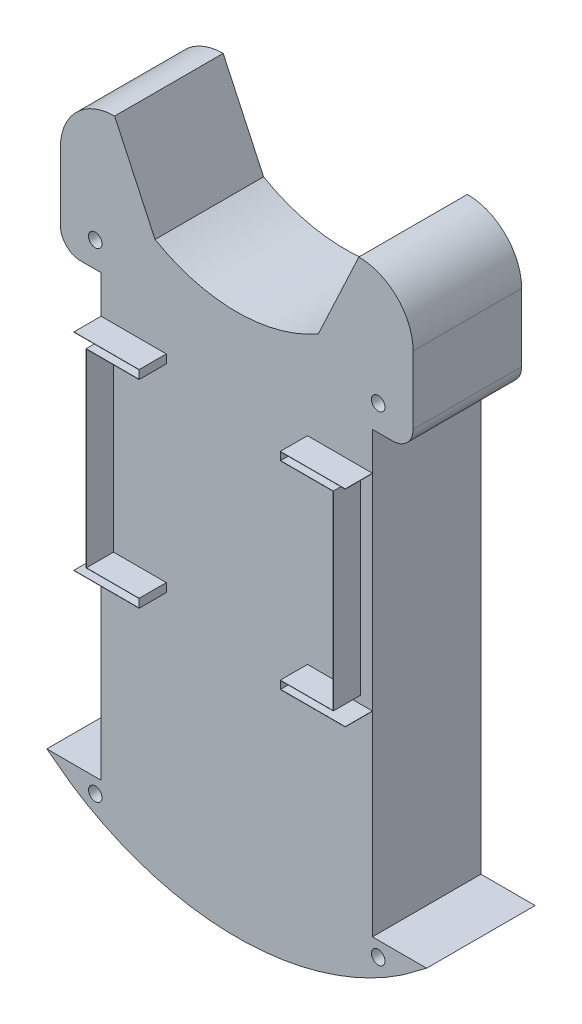
SolidWorks part; units mm, degrees
ref_plane "Front Plane" through (0, 0, 0) normal (0, 0, 1) x (1, 0, 0)
ref_plane "Top Plane" through (0, 0, 0) normal (0, 1, 0) x (1, 0, 0)
ref_plane "Right Plane" through (0, 0, 0) normal (1, 0, 0) x (0, 0, -1)
sketch "Sketch2" plane through (0, 0, 0) normal (0, 0, 1) x (1, 0, 0)
  line L1 (1270, 1959.5385) -> (1270, -2155.2615)
  line L2 (1270, -2155.2615) -> (1778, -2155.2615)
  line L3 (1778, -2155.2615) -> (1548.5652, -2325.5928)
  line L4 (0, 1050.9467) -> (0, -1390.1401) construction
  line L5 (1270, 1959.5385) -> (1460.5, 1959.5385)
  line L6 (1651, 2150.0385) -> (1651, 2785.0385)
  line L7 (-1778, -2155.2615) -> (-1548.5652, -2325.5928)
  line L8 (-1270, -2155.2615) -> (-1778, -2155.2615)
  line L9 (-1270, 1959.5385) -> (-1270, -2155.2615)
  line L10 (-1651, 2150.0385) -> (-1651, 2785.0385)
  line L11 (-1270, 1959.5385) -> (-1460.5, 1959.5385)
  line L12 (-1143, 3293.0385) -> (-764.6087, 2481.5759)
  line L14 (1143, 3293.0385) -> (764.6087, 2481.5759)
  line L15 (1143, 3293.0385) -> (1143, 2886.1422) construction
  arc A1 (1460.5, 1959.5385) -> (1651, 2150.0385) centre (1460.5, 2150.0385) ccw
  arc A2 (1651, 2785.0385) -> (1143, 3293.0385) centre (1143, 2785.0385) ccw
  arc A3 (-1651, 2785.0385) -> (-1143, 3293.0385) centre (-1143, 2785.0385) cw
  arc A4 (-1460.5, 1959.5385) -> (-1651, 2150.0385) centre (-1460.5, 2150.0385) cw
  arc A5 (-1778, -2155.2615) -> (1548.5652, -2325.5928) centre (0, 0) ccw
  arc A7 (-764.6087, 2481.5759) -> (764.6087, 2481.5759) centre (0, 3799.889) ccw
  point P21 (-1460.5, 1959.5385)
  dimension "D1" = 4114.8
  dimension "D4" = 2794
  dimension "D6" = 508
  dimension "D8" = 190.5
  dimension "D10" = 895.35
  dimension "D12" = 25
  dimension "D11" = 1524
  dimension "D13" = 2794
  dimension "D2" = 508
  dimension "D3" = 285.75
  dimension "D5" = 190.5
  dimension "D7" = 1270
  dimension "D9" = 635
extrude "Boss-Extrude1" add sketch "Sketch2" along normal blind 1016 contours A7 L12 A3 L10 A4 L11 L9 L8 L7 A5 L3 L2 L1 L5 A1 L6 A2 L14
sketch "Sketch5" plane through (0, 0, 1016) normal (0, 0, 1) x (1, 0, 0)
  line L0 (1270, -326.4615) -> (662.1255, -326.4615)
  line L1 (1270, 1959.5385) -> (1270, -2155.2615) construction
  line L3 (662.1255, -326.4615) -> (662.1255, -250.2615)
  line L6 (662.1255, -250.2615) -> (1155.7, -250.2615)
  line L7 (1155.7, -250.2615) -> (1155.7, 1527.7385)
  line L8 (1155.7, 1527.7385) -> (662.1255, 1527.7385)
  line L9 (662.1255, 1527.7385) -> (662.1255, 1603.9385)
  line L10 (662.1255, 1603.9385) -> (1270, 1603.9385)
  line L11 (1270, -2155.2615) -> (1778, -2155.2615) construction
  line L13 (0, 867.6729) -> (0, -443.3851) construction
  line L14 (-662.1255, 1603.9385) -> (-1270, 1603.9385)
  line L15 (-662.1255, 1527.7385) -> (-662.1255, 1603.9385)
  line L16 (-1155.7, 1527.7385) -> (-662.1255, 1527.7385)
  line L17 (-1155.7, -250.2615) -> (-1155.7, 1527.7385)
  line L18 (-662.1255, -250.2615) -> (-1155.7, -250.2615)
  line L19 (-662.1255, -326.4615) -> (-662.1255, -250.2615)
  line L20 (-1270, -326.4615) -> (-662.1255, -326.4615)
  dimension "D1" = 76.2
  dimension "D2" = 114.3
  dimension "D3" = 1828.8
  dimension "D4" = 1930.4
extrude "Extrude-Thin1" add sketch "Sketch5" along normal blind 254 thin
sketch "Sketch6" plane through (0, 0, 1016) normal (0, 0, 1) x (1, 0, 0)
  line L0 (0, 693.9813) -> (0, -470.7426) construction
  circle A0 centre (1324.2511, 2197.6963) radius 63.5
  circle A1 centre (1324.2511, -2292.873) radius 63.5
  circle A2 centre (-1324.2511, -2292.873) radius 63.5
  circle A3 centre (-1324.2511, 2197.6963) radius 63.5
extrude "Cut-Extrude1" cut sketch "Sketch6" against normal blind 2032
